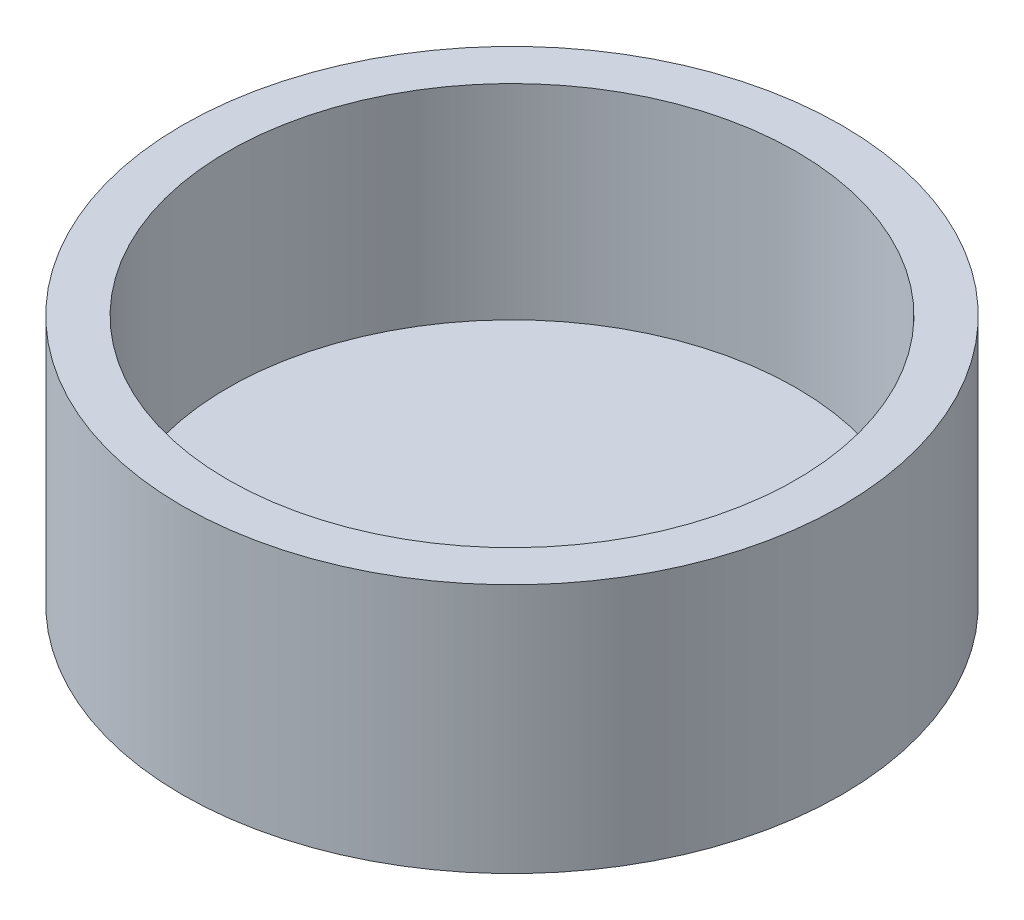
SolidWorks part; units mm, degrees
material "6061-T6 (SS)"
ref_plane "Front Plane" through (0, 0, 0) normal (0, 0, 1) x (1, 0, 0)
ref_plane "Top Plane" through (0, 0, 0) normal (0, 1, 0) x (1, 0, 0)
ref_plane "Right Plane" through (0, 0, 0) normal (1, 0, 0) x (0, 0, -1)
sketch "Sketch1" plane through (0, 0, 0) normal (0, 1, 0) x (1, 0, 0)
  circle A0 centre (0, 0) radius 31.75
  dimension "D1" = 63.5
extrude "Boss-Extrude2" add sketch "Sketch1" along normal blind 22.86 contours A0
shell "Shell3" thickness 5.08
